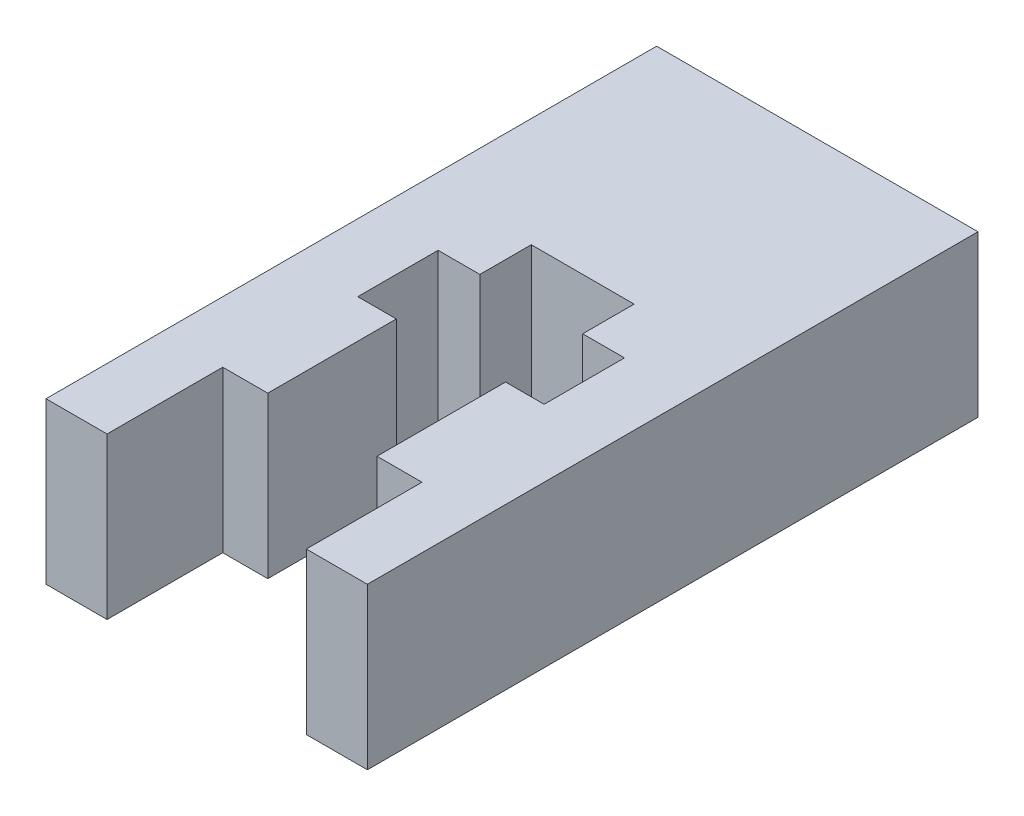
SolidWorks part; units mm, degrees
ref_plane "Front Plane" through (0, 0, 0) normal (0, 0, 1) x (1, 0, 0)
ref_plane "Top Plane" through (0, 0, 0) normal (0, 1, 0) x (1, 0, 0)
ref_plane "Right Plane" through (0, 0, 0) normal (1, 0, 0) x (0, 0, -1)
sketch "Sketch1" plane through (0, 0, 0) normal (0, 1, 0) x (1, 0, 0)
  line L0 (-5, -9.5) -> (-3.1, -9.5)
  line L1 (-5, -9.5) -> (-3.1, -9.5)
  line L2 (-5, -9.5) -> (-5, 9.5)
  line L3 (-5, 9.5) -> (5, 9.5)
  line L4 (5, -9.5) -> (5, 9.5)
  line L7 (-3.1, -9.5) -> (-3.1, -5.9)
  line L8 (-3.1, -5.9) -> (-1.7, -5.9)
  line L9 (-1.7, -5.9) -> (-1.7, -1.9)
  line L10 (-1.7, -1.9) -> (-2.9, -1.9)
  line L11 (-2.9, -1.9) -> (-2.9, 0.6)
  line L12 (-2.9, 0.6) -> (-1.6, 0.6)
  line L13 (-1.6, 0.6) -> (-1.6, 2.2)
  line L14 (-1.6, 2.2) -> (1.6, 2.2)
  line L16 (3.1, -9.5) -> (5, -9.5)
  line L17 (3.1, -9.5) -> (3.1, -5.9)
  line L18 (3.1, -5.9) -> (1.7, -5.9)
  line L19 (1.7, -5.9) -> (1.7, -1.9)
  line L20 (1.7, -1.9) -> (2.9, -1.9)
  line L21 (2.9, 0.6) -> (1.6, 0.6)
  line L22 (2.9, -1.9) -> (2.9, 0.6)
  line L23 (1.6, 0.6) -> (1.6, 2.2)
  point P0 (0, 0)
  dimension "D1" = 10
  dimension "D2" = 19
  dimension "D3" = 1.9
  dimension "D4" = 3.6
  dimension "D5" = 3.3
  dimension "D6" = 4
  dimension "D7" = 2.1
  dimension "D8" = 2.5
  dimension "D9" = 3.4
  dimension "D10" = 1.6
extrude "Boss-Extrude1" add sketch "Sketch1" along normal blind 5 contours L23 L21 L22 L20 L19 L18 L17 L16 L4 L3 L2 L0 L7 L8 L9 L10 L11 L12 L13 L14
